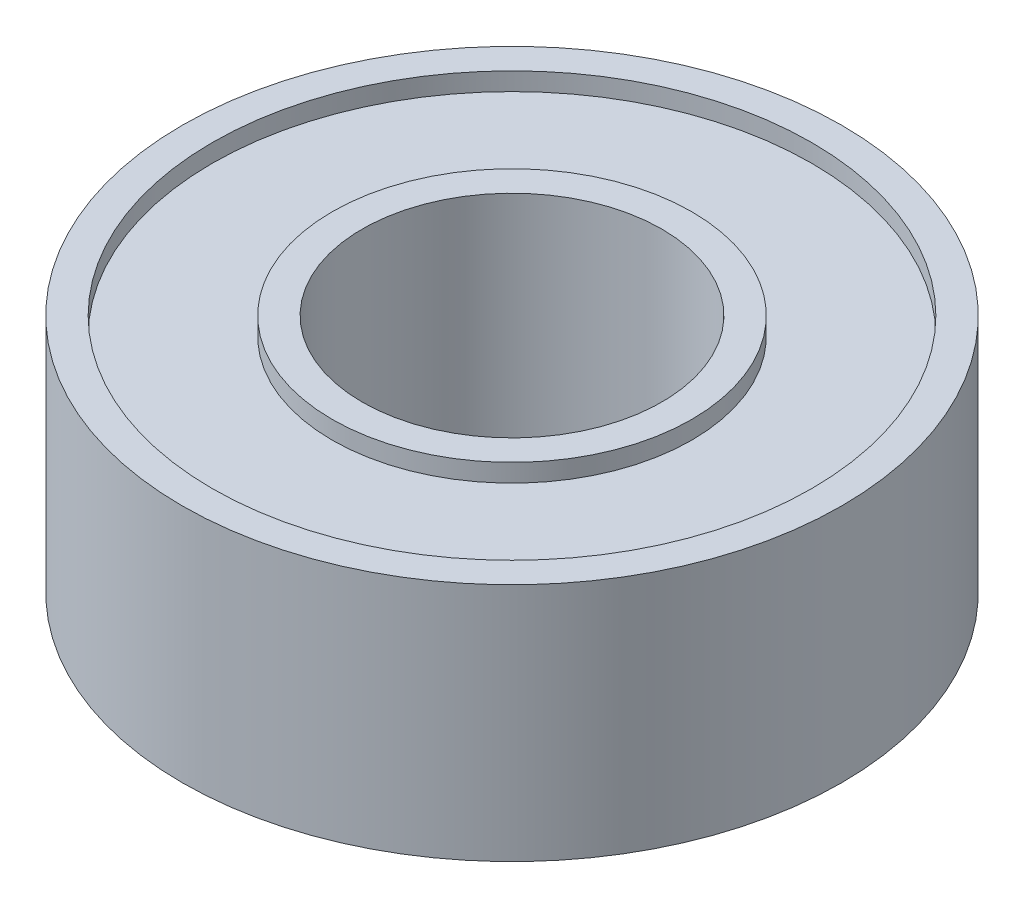
SolidWorks part; units mm, degrees
ref_plane "Front Plane" through (0, 0, 0) normal (0, 0, 1) x (1, 0, 0)
ref_plane "Top Plane" through (0, 0, 0) normal (0, 1, 0) x (1, 0, 0)
ref_plane "Right Plane" through (0, 0, 0) normal (1, 0, 0) x (0, 0, -1)
sketch "Sketch1" plane through (0, 0, 0) normal (0, 1, 0) x (1, 0, 0)
  circle A0 centre (0, 0) radius 2.5
  circle A1 centre (0, 0) radius 5.5
extrude "Boss-Extrude1" add sketch "Sketch1" along normal blind 4
sketch "Sketch2" plane through (0, 4, 0) normal (0, 1, 0) x (1, 0, 0)
  circle A0 centre (0, 0) radius 3
  circle A1 centre (0, 0) radius 5
extrude "Cut-Extrude1" cut sketch "Sketch2" against normal blind 0.3
sketch "Sketch3" plane through (0, 0, 0) normal (0, -1, 0) x (1, 0, 0)
  circle A0 centre (0, 0) radius 3
  circle A1 centre (0, 0) radius 5
extrude "Cut-Extrude2" cut sketch "Sketch3" against normal blind 0.3
